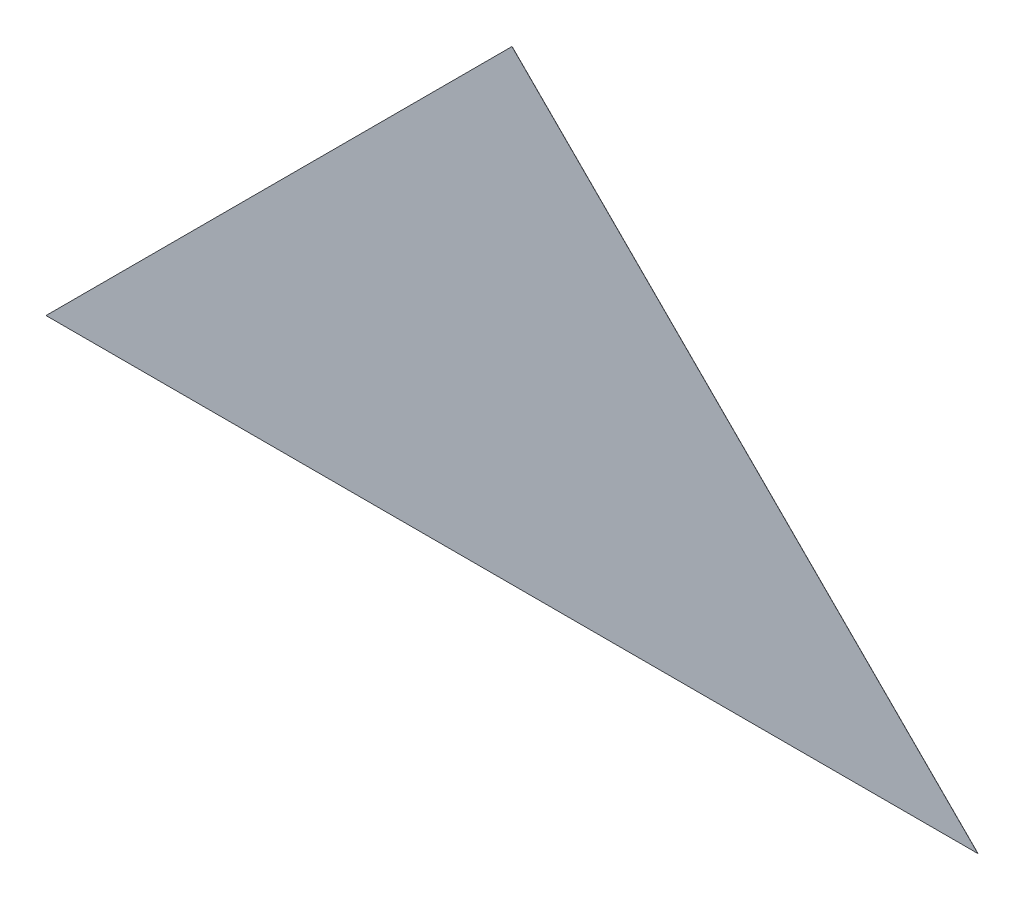
SolidWorks part; units mm, degrees
ref_plane "Front Plane" through (0, 0, 0) normal (0, 0, 1) x (1, 0, 0)
ref_plane "Top Plane" through (0, 0, 0) normal (0, 1, 0) x (1, 0, 0)
ref_plane "Right Plane" through (0, 0, 0) normal (1, 0, 0) x (0, 0, -1)
sketch "Sketch1" plane through (0, 0, 0) normal (0, 0, 1) x (1, 0, 0)
  line L0 (0, 0) -> (65, 0)
  line L1 (65, 0) -> (32.5, 32.5)
  line L2 (32.5, 32.5) -> (0, 0)
  line L3 (32.5, 32.5) -> (32.5, 0) construction
  dimension "D1" = 32.5
  dimension "D2" = 65
extrude "Boss-Extrude1" add sketch "Sketch1" along normal blind 0.01
